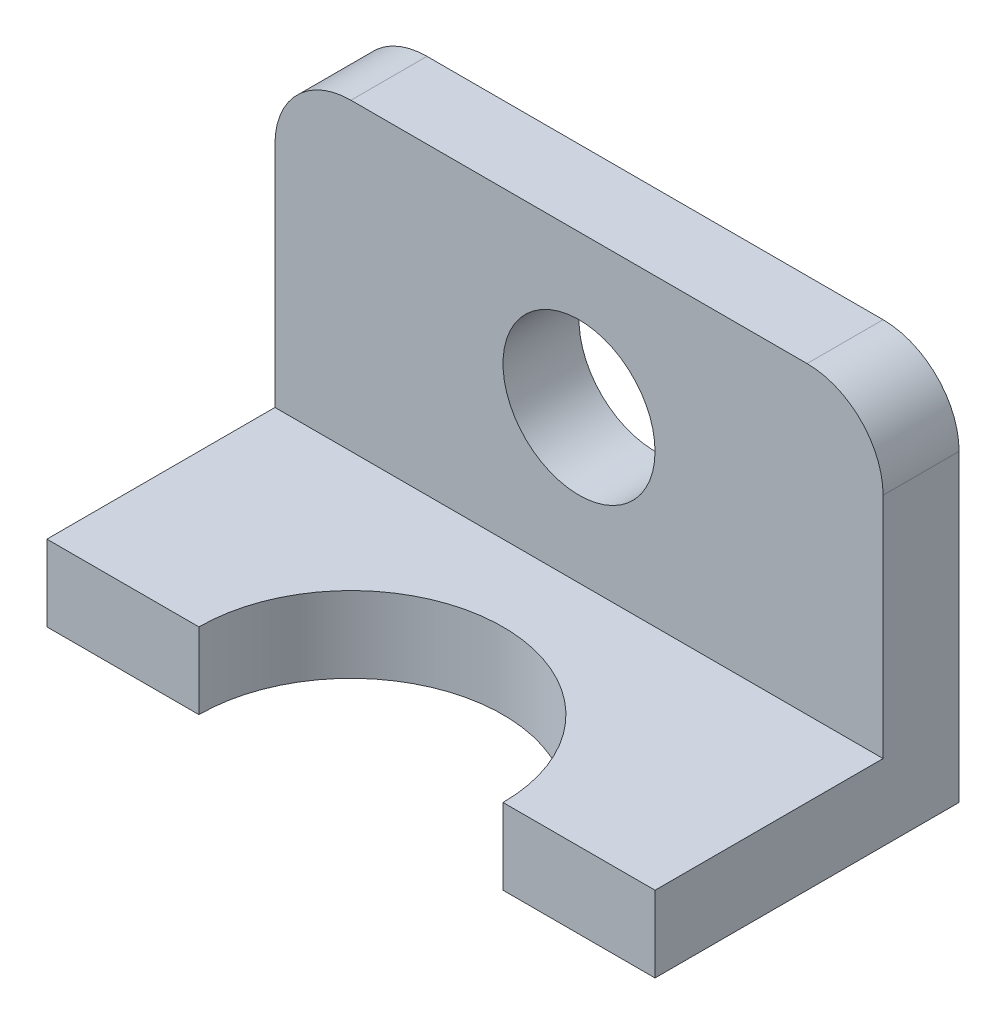
SolidWorks part; units mm, degrees
material "6061 Alloy"
ref_plane "Front Plane" through (0, 0, 0) normal (0, 0, 1) x (1, 0, 0)
ref_plane "Top Plane" through (0, 0, 0) normal (0, 1, 0) x (1, 0, 0)
ref_plane "Right Plane" through (0, 0, 0) normal (1, 0, 0) x (0, 0, -1)
sketch "Croquis1" plane through (0, 0, 0) normal (1, 0, 0) x (0, 0, -1)
  line L0 (0, 0) -> (0, 63.5)
  line L1 (0, 63.5) -> (-12.7, 63.5)
  line L2 (-12.7, 63.5) -> (-12.7, 12.7)
  line L3 (-12.7, 12.7) -> (-50.8, 12.7)
  line L4 (-50.8, 12.7) -> (-50.8, 0)
  line L5 (-50.8, 0) -> (0, 0)
  dimension "D1" = 63.5
  dimension "D2" = 50.8
  dimension "D3" = 12.7
  dimension "D4" = 12.7
extrude "Saliente-Extruir1" add sketch "Croquis1" along normal blind 101.6
sketch "Croquis2" plane through (0, 12.7, 0) normal (0, 1, 0) x (1, 0, 0)
  line L0 (101.6, -50.8) -> (0, -50.8) construction
  circle A0 centre (50.8, -50.8) radius 25.4
  dimension "D1" = 50.8
extrude "Cortar-Extruir1" cut sketch "Croquis2" against normal blind 101.6
sketch "Croquis3" plane through (0, 0, 12.7) normal (0, 0, 1) x (1, 0, 0)
  line L0 (50.8, 63.5) -> (50.8, 12.7) construction
  line L1 (101.6, 63.5) -> (0, 63.5) construction
  line L2 (76.2, 12.7) -> (25.4, 12.7) construction
  circle A0 centre (50.8, 38.1) radius 12.7
  dimension "D1" = 25.4
extrude "Cortar-Extruir2" cut sketch "Croquis3" against normal blind 101.6
fillet "Redondeo1" radius 12.7 2 edges at (0, 63.5, 6.35) (101.6, 63.5, 6.35)
